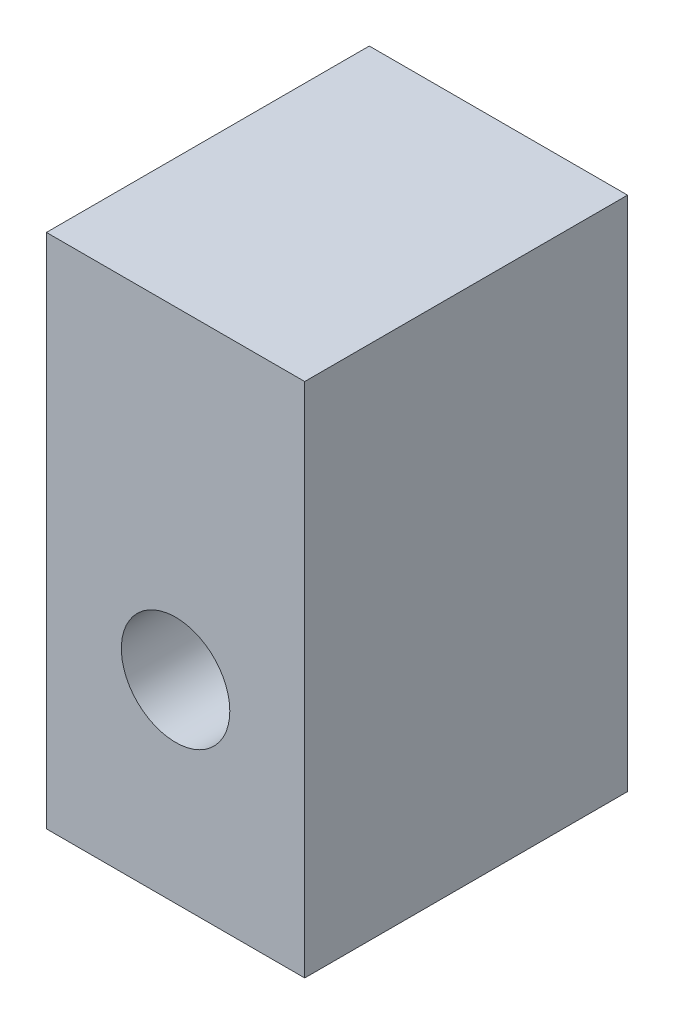
SolidWorks part; units mm, degrees
ref_plane "Front Plane" through (0, 0, 0) normal (0, 0, 1) x (1, 0, 0)
ref_plane "Top Plane" through (0, 0, 0) normal (0, 1, 0) x (1, 0, 0)
ref_plane "Right Plane" through (0, 0, 0) normal (1, 0, 0) x (0, 0, -1)
sketch "Sketch1" plane through (0, 0, 0) normal (0, 1, 0) x (1, 0, 0)
  line L1 (-25.4, -31.75) -> (25.4, -31.75)
  line L2 (-25.4, -31.75) -> (-25.4, 31.75)
  line L3 (-25.4, 31.75) -> (25.4, 31.75)
  line L4 (25.4, -31.75) -> (25.4, 31.75)
  line L5 (-25.4, -31.75) -> (25.4, 31.75) construction
  line L6 (-25.4, 31.75) -> (25.4, -31.75) construction
  point P0 (0, 0)
  dimension "D1" = 63.5
  dimension "D2" = 50.8
extrude "Boss-Extrude2" add sketch "Sketch1" along normal blind 101.6
sketch "Sketch4" plane through (0, 0, 0) normal (0, 0, 1) x (1, 0, 0)
  circle A0 centre (0, 38.1) radius 10.668
  dimension "D1" = 21.336
  dimension "D2" = 38.1
extrude "Cut-Extrude2" cut sketch "Sketch4" against normal through all both and the other way through all
